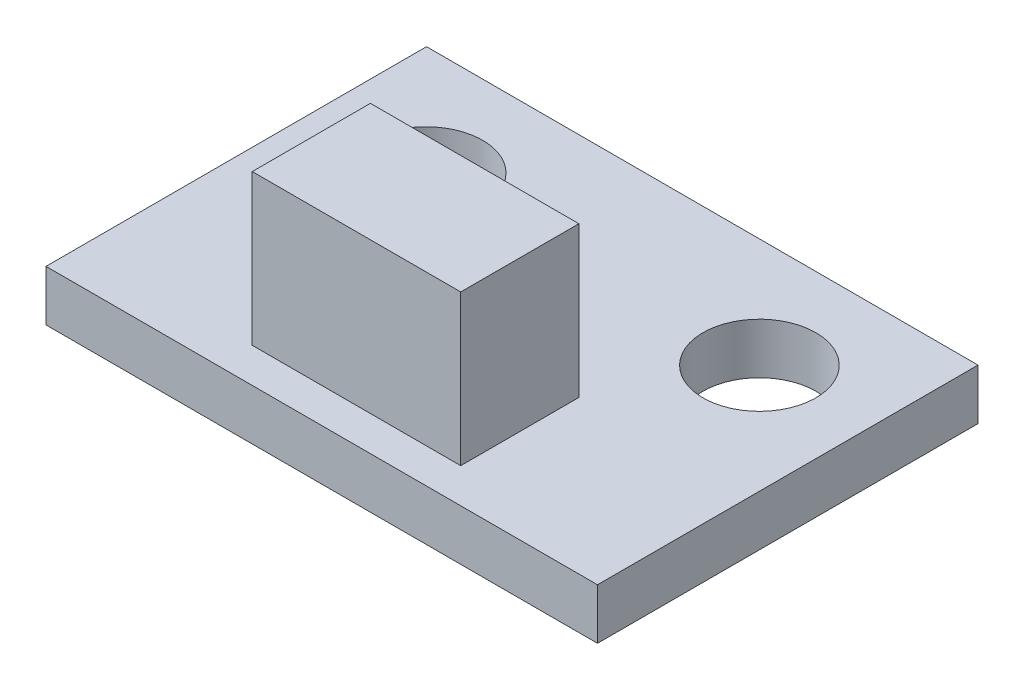
SolidWorks part; units mm, degrees
ref_plane "Front Plane" through (0, 0, 0) normal (0, 0, 1) x (1, 0, 0)
ref_plane "Top Plane" through (0, 0, 0) normal (0, 1, 0) x (1, 0, 0)
ref_plane "Right Plane" through (0, 0, 0) normal (1, 0, 0) x (0, 0, -1)
sketch "Sketch1" plane through (0, 0, 0) normal (0, 1, 0) x (1, 0, 0)
  line L0 (0, 0) -> (0, 5.475) construction
  line L1 (7.935, 5.475) -> (-7.935, 5.475)
  line L2 (7.935, 5.475) -> (7.935, -5.475)
  line L3 (7.935, -5.475) -> (-7.935, -5.475)
  line L4 (-7.935, 5.475) -> (-7.935, -5.475)
  line L5 (7.935, 5.475) -> (-7.935, -5.475) construction
  line L6 (7.935, -5.475) -> (-7.935, 5.475) construction
  circle A0 centre (-4.795, 2.325) radius 1.625
  circle A1 centre (4.795, 2.325) radius 1.625
  point P0 (0, 0)
  dimension "D3" = 3.25
  dimension "D1" = 15.87
  dimension "D2" = 10.95
  dimension "D4" = 3.14
  dimension "D5" = 3.15
extrude "Boss-Extrude1" add sketch "Sketch1" along normal blind 1.46
sketch "Sketch2" plane through (0, 1.46, 0) normal (0, 1, 0) x (1, 0, 0)
  line L0 (0, 0) -> (0, 5.475) construction
  line L1 (-3, -1.075) -> (3, -1.075)
  line L2 (-3, -1.075) -> (-3, -4.475)
  line L3 (-3, -4.475) -> (3, -4.475)
  line L4 (3, -1.075) -> (3, -4.475)
  line L5 (7.935, 5.475) -> (-7.935, 5.475) construction
  line L6 (-7.935, -5.475) -> (7.935, -5.475) construction
  dimension "D1" = 3.4
  dimension "D2" = 6
  dimension "D3" = 1
extrude "Boss-Extrude2" add sketch "Sketch2" along normal blind 4.33
